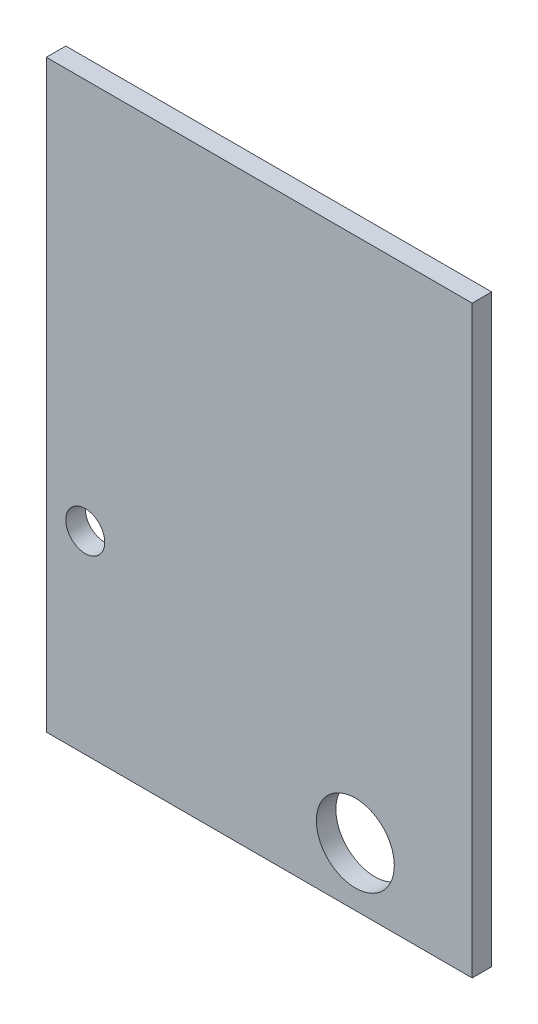
SolidWorks part; units mm, degrees
ref_plane "Front Plane" through (0, 0, 0) normal (0, 0, 1) x (1, 0, 0)
ref_plane "Top Plane" through (0, 0, 0) normal (0, 1, 0) x (1, 0, 0)
ref_plane "Right Plane" through (0, 0, 0) normal (1, 0, 0) x (0, 0, -1)
sketch "Sketch1" plane through (0, 0, 0) normal (0, 0, 1) x (1, 0, 0)
  line L0 (-138.63, 69.36) -> (-138.63, 0) construction
  line L1 (-158.63, 270) -> (60, 270)
  line L2 (-158.63, 270) -> (-158.63, -30)
  line L3 (-158.63, -30) -> (60, -30)
  line L4 (60, 270) -> (60, -30)
  line L5 (-138.63, 0) -> (0, 0) construction
  circle A0 centre (0, 0) radius 20
  circle A1 centre (-138.63, 69.36) radius 10
  dimension "D1" = 40
  dimension "D2" = 20
  dimension "D3" = 138.63
  dimension "D4" = 69.36
  dimension "D5" = 60
  dimension "D6" = 30
  dimension "D7" = 10
  dimension "D8" = 300
extrude "Boss-Extrude1" add sketch "Sketch1" along normal blind 10
